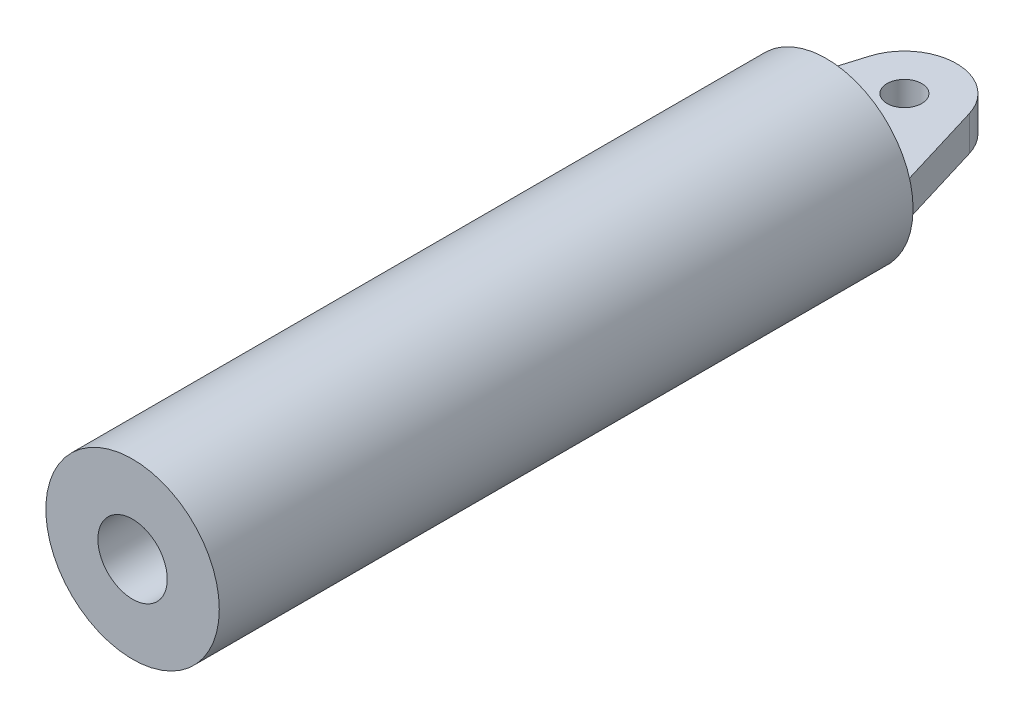
SolidWorks part; units mm, degrees
ref_plane "Front Plane" through (0, 0, 0) normal (0, 0, 1) x (1, 0, 0)
ref_plane "Top Plane" through (0, 0, 0) normal (0, 1, 0) x (1, 0, 0)
ref_plane "Right Plane" through (0, 0, 0) normal (1, 0, 0) x (0, 0, -1)
sketch "Sketch1" plane through (0, 0, 0) normal (0, 0, 1) x (1, 0, 0)
  circle A0 centre (0, 0) radius 50
  dimension "D1" = 100
extrude "Boss-Extrude1" add sketch "Sketch1" along normal blind 400
shell "Shell1" thickness 30
sketch "Sketch2" plane through (0, 0, 0) normal (0, 1, 0) x (1, 0, 0)
  line L0 (-45, 0) -> (-28.7083, 53.7083)
  line L1 (50, 0) -> (-50, 0) construction
  line L2 (28.7083, 53.7083) -> (45, 0)
  line L3 (-45, 0) -> (45, 0)
  circle A0 centre (0, 45) radius 10
  arc A1 (-28.7083, 53.7083) -> (28.7083, 53.7083) centre (0, 45) cw
  dimension "D1" = 30
  dimension "D2" = 20
  dimension "D3" = 45
  dimension "D4" = 45
  dimension "D5" = 45
extrude "Boss-Extrude2" add sketch "Sketch2" along normal mid plane 20
